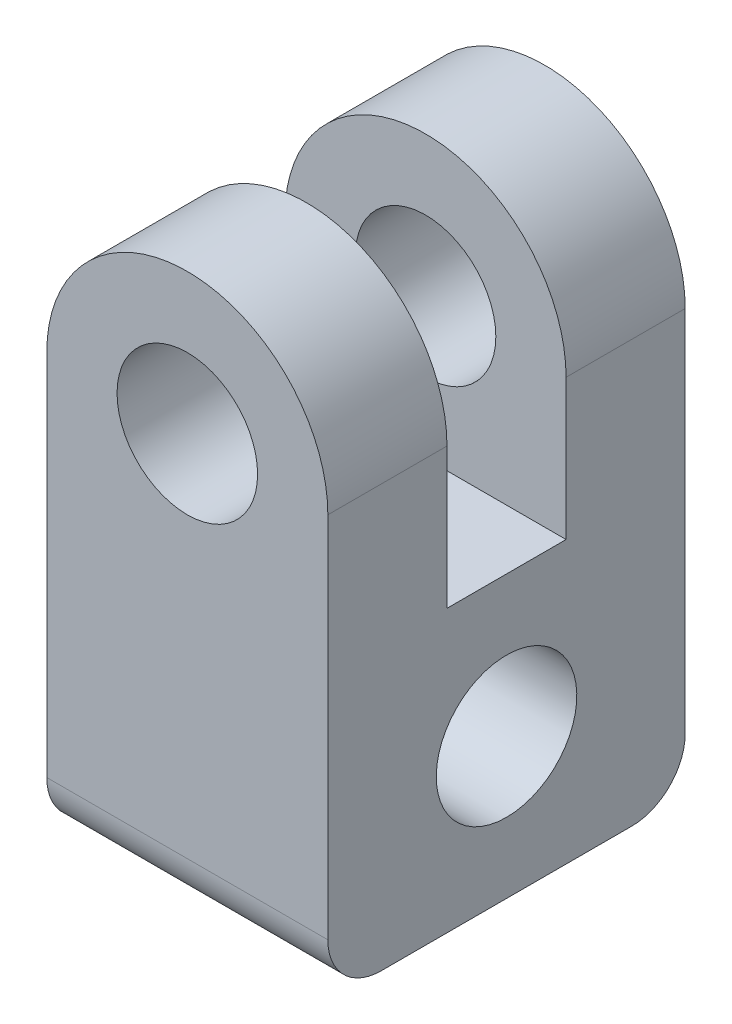
SolidWorks part; units mm, degrees
ref_plane "Front Plane" through (0, 0, 0) normal (0, 0, 1) x (1, 0, 0)
ref_plane "Top Plane" through (0, 0, 0) normal (0, 1, 0) x (1, 0, 0)
ref_plane "Right Plane" through (0, 0, 0) normal (1, 0, 0) x (0, 0, -1)
sketch "Sketch1" plane through (0, 0, 0) normal (0, 0, 1) x (1, 0, 0)
  line L0 (-52.5, 0) -> (-52.5, -157.5)
  line L1 (-52.5, -157.5) -> (52.5, -157.5)
  line L2 (52.5, -157.5) -> (52.5, 0)
  circle A0 centre (0, 0) radius 26.25
  arc A2 (-52.5, 0) -> (52.5, 0) centre (0, 0) cw
  dimension "D1" = 52.5
  dimension "D2" = 157.5
  dimension "D3" = 105
extrude "Boss-Extrude1" add sketch "Sketch1" along normal blind 133.5
sketch "Sketch3" plane through (-52.5, 0, 0) normal (-1, 0, 0) x (0, 0, 1)
  line L0 (0, 0) -> (0, -157.5) construction
  line L1 (133.5, -157.5) -> (0, -157.5) construction
  circle A0 centre (66.75, -105) radius 26.25
  dimension "D1" = 52.5
  dimension "D2" = 66.75
  dimension "D3" = 52.5
extrude "Cut-Extrude1" cut sketch "Sketch3" against normal through all
sketch "Sketch6" plane through (0, -157.5, 0) normal (0, -1, 0) x (1, 0, 0)
  line L0 (-52.5, 66.75) -> (-52.5, 44.5)
  line L1 (-52.5, 133.5) -> (-52.5, 0) construction
  line L2 (-52.5, 66.75) -> (-52.5, 89)
  line L3 (-52.5, 89) -> (52.5, 89)
  line L4 (52.5, 133.5) -> (52.5, 0) construction
  line L5 (52.5, 89) -> (52.5, 44.5)
  line L6 (52.5, 44.5) -> (-52.5, 44.5)
extrude "Cut-Extrude2" cut sketch "Sketch6" along normal blind 105 from offset 210 offset against normal yes
fillet "Fillet1" radius 20 2 edges at (0, -157.5, 133.5) (0, -157.5, 0)
